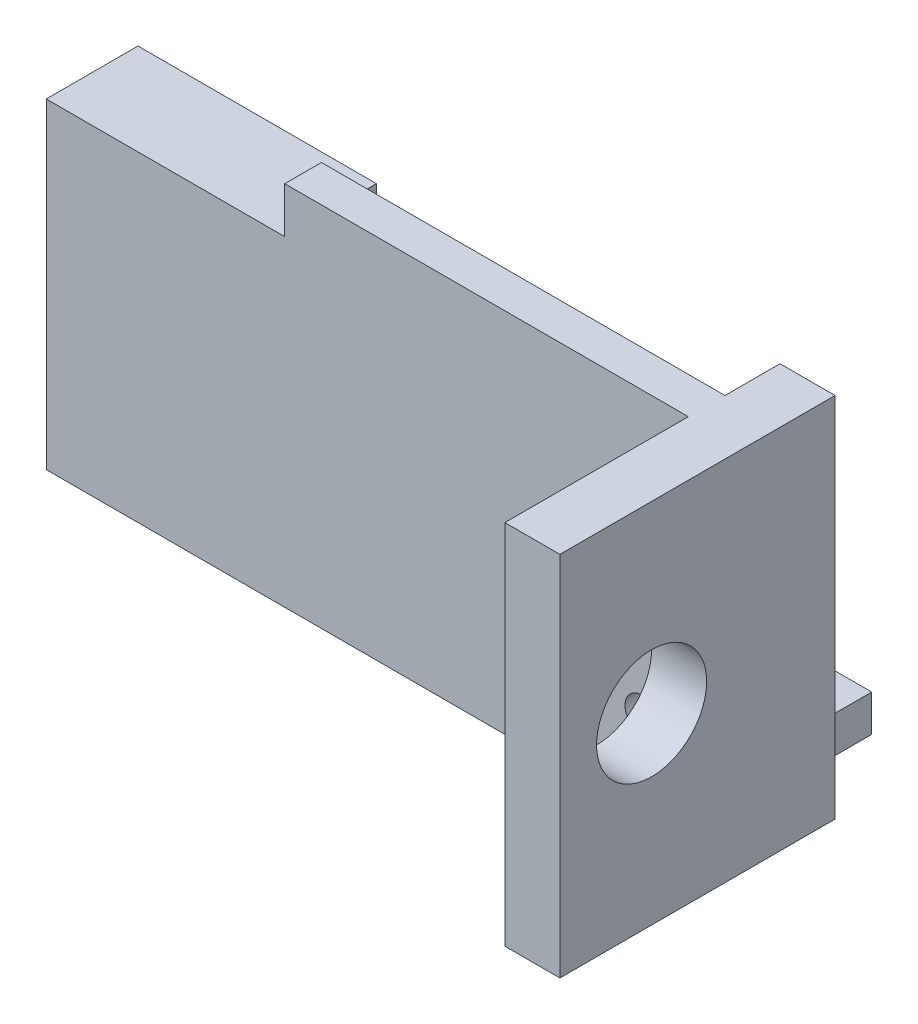
SolidWorks part; units mm, degrees
ref_plane "前视基准面" through (0, 0, 0) normal (0, 0, 1) x (1, 0, 0)
ref_plane "上视基准面" through (0, 0, 0) normal (0, 1, 0) x (1, 0, 0)
ref_plane "右视基准面" through (0, 0, 0) normal (1, 0, 0) x (0, 0, -1)
other "Configuration Table"
sketch "草图1" plane through (0, 0, 0) normal (0, 0, 1) x (1, 0, 0)
  line L0 (-17.5, 6.5) -> (-4.5, 6.5)
  line L1 (-4.5, 9) -> (17.5, 9)
  line L2 (-17.5, 6.5) -> (-17.5, -9)
  line L3 (-17.5, -9) -> (17.5, -9)
  line L4 (17.5, 9) -> (17.5, -9)
  line L7 (-4.5, 6.5) -> (-4.5, 9)
  circle A0 centre (15, -6.35) radius 0.95
  point P0 (0, 0)
  dimension "D9" = 1.9
  dimension "D1" = 35
  dimension "D2" = 18
  dimension "D3" = 13
  dimension "D4" = 2.5
  dimension "D5" = 17.5
  dimension "D6" = 9
  dimension "D7" = 2.5
  dimension "D8" = 2.65
extrude "凸台-拉伸1" add sketch "草图1" along normal blind 2
sketch "草图2" plane through (0, 0, 0) normal (0, 0, -1) x (-1, 0, 0)
  line L0 (4.5, 9) -> (4.5, 6.5) construction
  line L1 (-17.5, -9) -> (-9.5, -9)
  line L2 (-17.5, -9) -> (-17.5, -4)
  line L3 (-17.5, -4) -> (-9.5, -4)
  line L4 (-9.5, -9) -> (-9.5, -4)
  line L5 (17.5, 6.5) -> (4.5, 6.5)
  line L6 (17.5, 6.5) -> (17.5, 3)
  line L7 (17.5, 3) -> (4.5, 3)
  line L8 (4.5, 6.5) -> (4.5, 3)
  circle A1 centre (-15, -6.35) radius 0.95
  dimension "D1" = 8
  dimension "D2" = 5
  dimension "D3" = 3.5
extrude "凸台-拉伸2" add sketch "草图2" along normal blind 3
sketch "草图4" plane through (0, -9, 0) normal (0, -1, 0) x (1, 0, 0)
  line L0 (-17.5, -3) -> (-17.5, 0) construction
  line L1 (17.5, 2) -> (-17.5, 2)
  line L2 (17.5, 2) -> (17.5, -8)
  line L3 (17.5, -8) -> (-17.5, -8)
  line L4 (-17.5, 2) -> (-17.5, -8)
  line L5 (-4.5, -3) -> (-17.5, -3) construction
  dimension "D1" = 5
extrude "凸台-拉伸3" add sketch "草图4" along normal blind 2
sketch "草图5" plane through (17.5, 0, 0) normal (1, 0, 0) x (0, 0, -1)
  line L0 (3.0007, -2.9899) -> (5.8053, -50002.9898) construction
  line L2 (-1, 9) -> (49999, 9) construction
  line L3 (-2, 9) -> (0, 9) construction
  line L4 (8, -11) -> (-2, -11) construction
  line L5 (3, 9) -> (-12, 9)
  line L6 (3, 9) -> (3, -11)
  line L7 (3, -11) -> (-12, -11)
  line L8 (-12, 9) -> (-12, -11)
  line L9 (-20.9472, -1) -> (49979.0528, -1) construction
  line L10 (-2, -11) -> (-2, 9) construction
  line L11 (3, -4) -> (3, -9) construction
  circle A0 centre (-7, -1) radius 3
  point P6 (-1, 9)
  dimension "D3" = 6
  dimension "D1" = 10
  dimension "D2" = 10
  dimension "D4" = 5
extrude "凸台-拉伸4" add sketch "草图5" along normal blind 3
